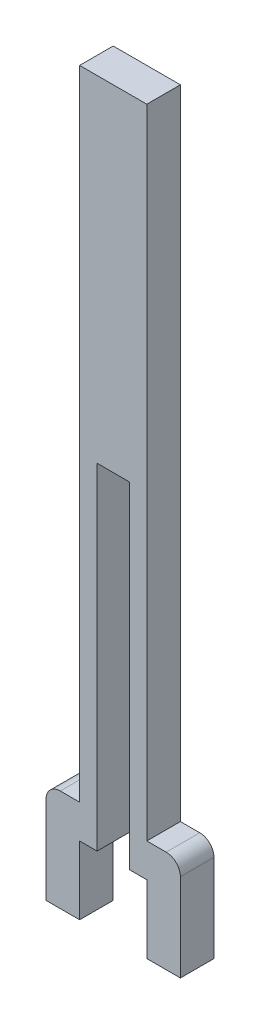
SolidWorks part; units mm, degrees
ref_plane "Front Plane" through (0, 0, 0) normal (0, 0, 1) x (1, 0, 0)
ref_plane "Top Plane" through (0, 0, 0) normal (0, 1, 0) x (1, 0, 0)
ref_plane "Right Plane" through (0, 0, 0) normal (1, 0, 0) x (0, 0, -1)
sketch "스케치1" plane through (0, 0, 0) normal (0, 0, 1) x (1, 0, 0)
  line L0 (0, 0) -> (0, -26.944) construction
  line L1 (-6, -33.044) -> (6, -33.044) construction
  line L2 (-6, -33.044) -> (-6, 33.044) construction
  line L3 (-6, 33.044) -> (6, 33.044) construction
  line L4 (6, -33.044) -> (6, 33.044) construction
  line L5 (-6, -33.044) -> (6, 33.044) construction
  line L6 (-6, 33.044) -> (6, -33.044) construction
  line L7 (-3, -33.044) -> (3, -33.044) construction
  line L8 (-3, -33.044) -> (-3, -26.944)
  line L9 (-3, -26.944) -> (3, -26.944)
  line L10 (3, -33.044) -> (3, -26.944)
  line L11 (-3, -33.044) -> (3, -26.944) construction
  line L12 (-3, -26.944) -> (3, -33.044) construction
  line L13 (3, -23.944) -> (-3, -23.944) construction
  line L14 (6, -23.944) -> (3, -23.944)
  line L15 (6, -23.944) -> (6, 33.044) construction
  line L16 (6, 33.044) -> (3, 33.044) construction
  line L17 (3, -23.944) -> (3, 33.044) construction
  line L18 (6, -23.944) -> (3, 33.044) construction
  line L19 (6, 33.044) -> (3, -23.944) construction
  line L20 (-3, 33.044) -> (-6, 33.044) construction
  line L21 (-3, 33.044) -> (-3, -23.944) construction
  line L22 (-3, -23.944) -> (-6, -23.944)
  line L23 (-6, 33.044) -> (-6, -23.944) construction
  line L24 (-3, 33.044) -> (-6, -23.944) construction
  line L25 (-3, -23.944) -> (-6, 33.044) construction
  line L26 (3, -33.044) -> (6, -33.044)
  line L27 (-1.5, 23.944) -> (1.5, 23.944) construction
  line L28 (-1.5, 23.944) -> (-1.5, -23.944) construction
  line L29 (-1.5, -23.944) -> (1.5, -23.944) construction
  line L30 (1.5, 23.944) -> (1.5, -23.944) construction
  line L31 (-1.5, 23.944) -> (1.5, -23.944) construction
  line L32 (-1.5, -23.944) -> (1.5, 23.944) construction
  line L33 (6, -33.044) -> (6, -23.944)
  line L34 (-6, -23.944) -> (-6, -33.044)
  line L35 (-6, -33.044) -> (-3, -33.044)
  line L36 (-3, 33.044) -> (-6, 33.044) construction
  line L37 (-6, 33.044) -> (-6, -33.044)
  line L38 (3, 33.044) -> (6, 33.044) construction
  line L39 (-3, -23.944) -> (-3, 33.044)
  line L40 (3, 33.044) -> (3, -23.944)
  line L41 (-3, 33.044) -> (3, 33.044)
  point P0 (0, 0)
  point P10 (0, -29.994)
  point P16 (4.5, 4.55)
  point P20 (-4.5, 4.55)
  dimension "D1" = 66.088
  dimension "D2" = 12
  dimension "D3" = 6
  dimension "D4" = 6.1
  dimension "D5" = 6
  dimension "D6" = 3
  dimension "D7" = 3
extrude "보스-돌출1" add sketch "스케치1" along normal blind 3 contours L41 L39 L22 L34 L35 L8 L9 L10 L26 L33 L14 L40
fillet "필렛1" radius 1.27 2 edges at (6, -23.944, 1.5) (-6, -23.944, 1.5)
sketch "스케치2" plane through (0, 0, 0) normal (0, 0, -1) x (-1, 0, 0)
  line L0 (0, 33.044) -> (0, -26.944) construction
  line L1 (3, 33.044) -> (-3, 33.044) construction
  line L2 (3, -26.944) -> (-3, -26.944) construction
  line L4 (-1.44, -26.944) -> (1.44, -26.944)
  line L5 (-1.44, -26.944) -> (-1.44, 3.05)
  line L6 (-1.44, 3.05) -> (1.44, 3.05)
  line L7 (1.44, -26.944) -> (1.44, 3.05)
  line L8 (-1.44, -26.944) -> (1.44, 3.05) construction
  line L9 (-1.44, 3.05) -> (1.44, -26.944) construction
  point P6 (0, -11.947)
  point P11 (0, 3.05)
  dimension "D1" = 2.88
extrude "컷-돌출1" cut sketch "스케치2" against normal up to surface (3 mm away) up to face at (0, -18.9753, 3)
